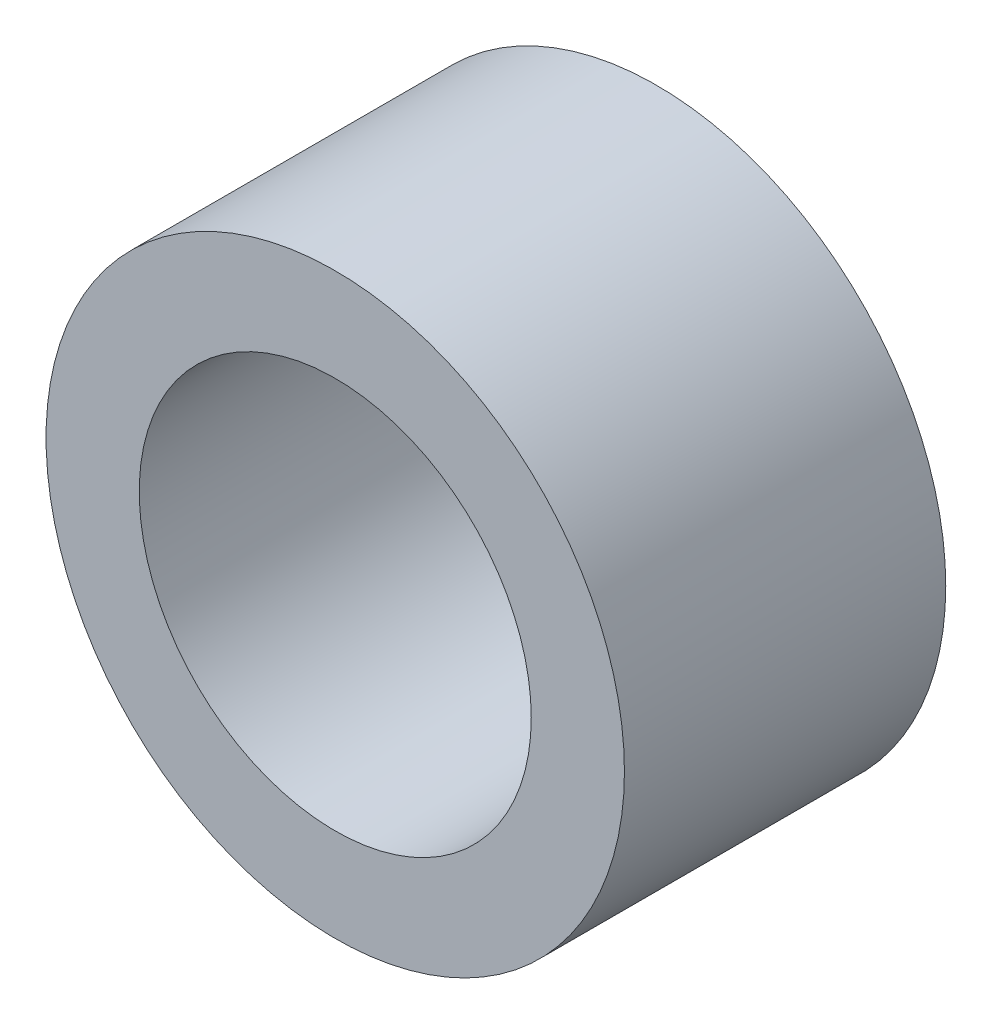
SolidWorks part; units mm, degrees
ref_plane "Front Plane" through (0, 0, 0) normal (0, 0, 1) x (1, 0, 0)
ref_plane "Top Plane" through (0, 0, 0) normal (0, 1, 0) x (1, 0, 0)
ref_plane "Right Plane" through (0, 0, 0) normal (1, 0, 0) x (0, 0, -1)
sketch "Sketch1" plane through (0, 0, 0) normal (0, 0, 1) x (1, 0, 0)
  circle A0 centre (0, 0) radius 3.05
  circle A1 centre (0, 0) radius 4.5
  dimension "D1" = 9
  dimension "D2" = 6.1
extrude "Boss-Extrude1" add sketch "Sketch1" along normal blind 5
